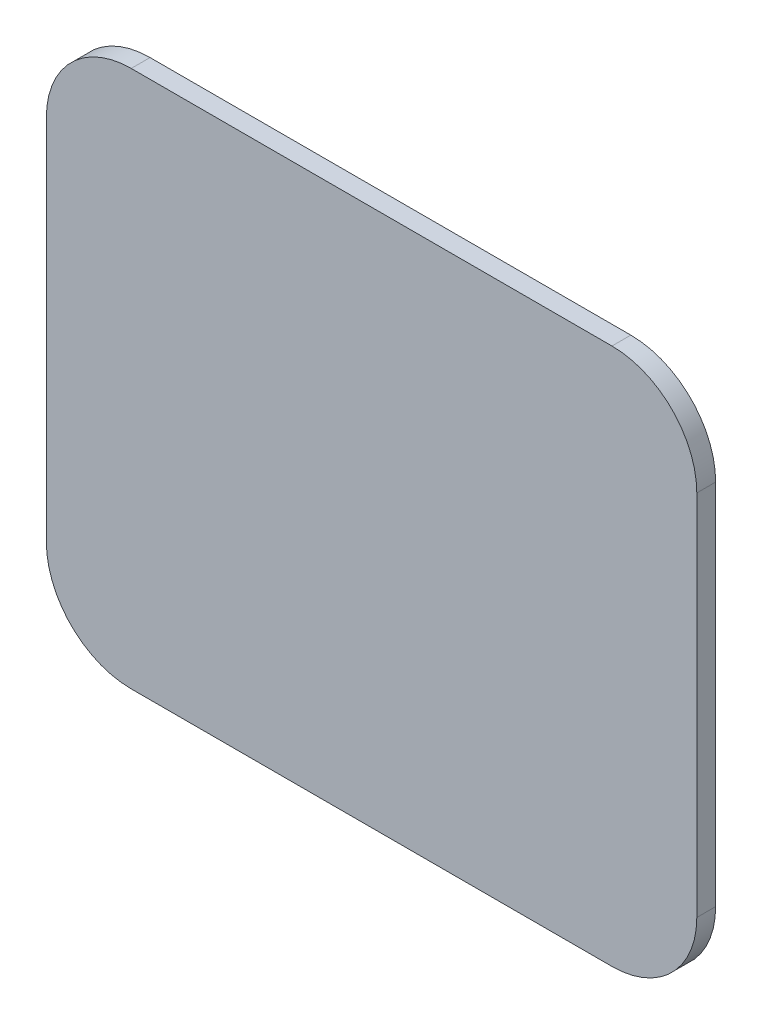
SolidWorks part; units mm, degrees
ref_plane "前视基准面" through (0, 0, 0) normal (0, 0, 1) x (1, 0, 0)
ref_plane "上视基准面" through (0, 0, 0) normal (0, 1, 0) x (1, 0, 0)
ref_plane "右视基准面" through (0, 0, 0) normal (1, 0, 0) x (0, 0, -1)
other "Configuration Table"
sketch "草图1" plane through (0, 0, 0) normal (0, 0, 1) x (1, 0, 0)
  line L1 (0, 0) -> (34.5, 0)
  line L2 (0, 0) -> (0, 28.5)
  line L3 (0, 28.5) -> (34.5, 28.5)
  line L4 (34.5, 0) -> (34.5, 28.5)
  dimension "D1" = 34.5
  dimension "D2" = 28.5
extrude "凸台-拉伸1" add sketch "草图1" along normal blind 1
fillet "圆角1" radius 4.5 4 edges at (34.5, 28.5, 0.5) (34.5, 0, 0.5) (0, 0, 0.5) (0, 28.5, 0.5)
